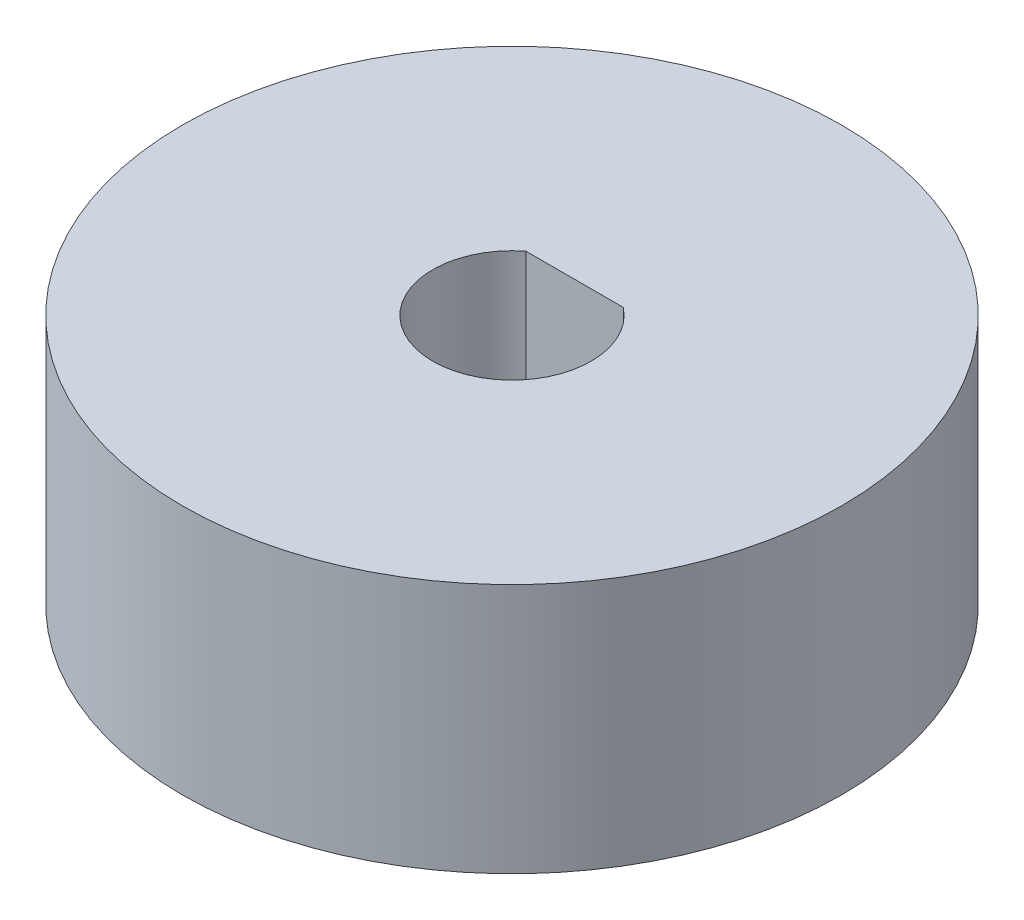
SolidWorks part; units mm, degrees
ref_plane "前视基准面" through (0, 0, 0) normal (0, 0, 1) x (1, 0, 0)
ref_plane "上视基准面" through (0, 0, 0) normal (0, 1, 0) x (1, 0, 0)
ref_plane "右视基准面" through (0, 0, 0) normal (1, 0, 0) x (0, 0, -1)
other "Configuration Table"
sketch "草图1" plane through (0, 0, 0) normal (0, 1, 0) x (1, 0, 0)
  line L0 (0, -1.9883) -> (0, -1.9)
  line L1 (-1.1662, 1.5) -> (1.1662, 1.5)
  circle A0 centre (0, 0) radius 7.9
  circle A1 centre (0, 0) radius 1.9
  dimension "D1" = 15.8
  dimension "D2" = 3.8
  dimension "D3" = 3.4
extrude "凸台-拉伸3" add sketch "草图1" along normal blind 6 contours A0 A1 | L1 A1
